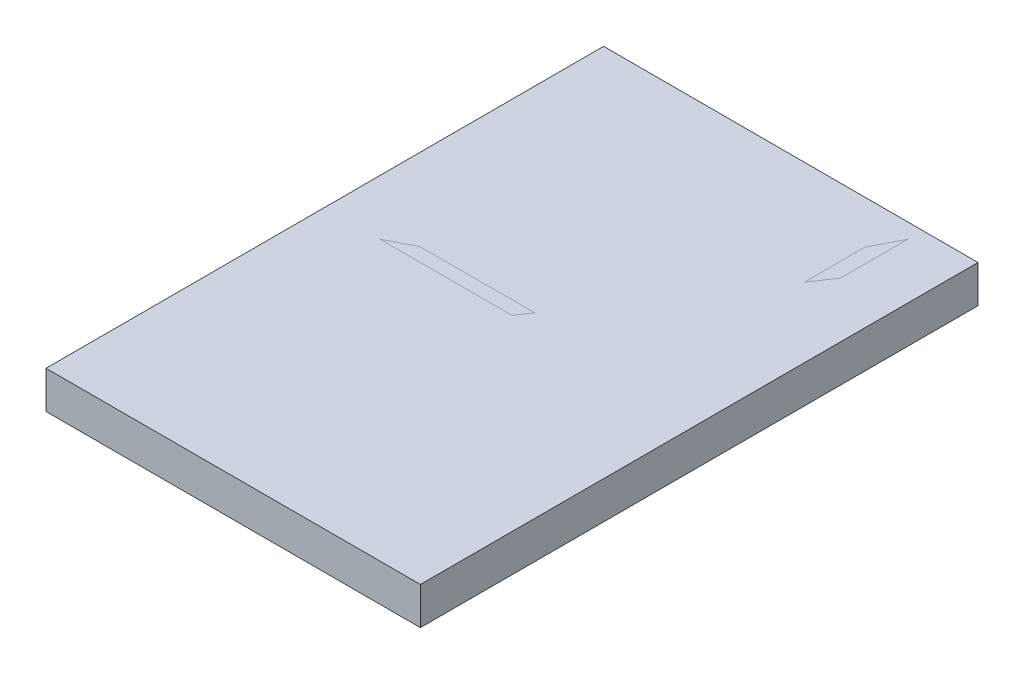
SolidWorks part; units mm, degrees
other "Stock"
other "Part"
ref_plane "Front Plane" through (0, 0, 0) normal (0, 0, 1) x (1, 0, 0)
ref_plane "Top Plane" through (0, 0, 0) normal (0, 1, 0) x (1, 0, 0)
ref_plane "Right Plane" through (0, 0, 0) normal (1, 0, 0) x (0, 0, -1)
sketch "Sketch1" plane through (0, 0, 0) normal (0, 1, 0) x (1, 0, 0)
  line L0 (28.2, 0) -> (28.2, -142.8) construction
  line L1 (0, 0) -> (56.4, 0)
  line L2 (0, 0) -> (0, -142.8)
  line L3 (0, -142.8) -> (56.4, -142.8)
  line L4 (56.4, 0) -> (56.4, -142.8)
  line L5 (0, -71.4) -> (56.4, -71.4) construction
  dimension "D1" = 56.4
  dimension "D2" = 142.8
extrude "Boss-Extrude1" add sketch "Sketch1" along normal blind 8
sketch "Sketch2" plane through (0, 8, 0) normal (0, 1, 0) x (1, 0, 0)
  line L0 (0, -71.4) -> (56.4, -71.4) construction
  line L1 (0, 0) -> (0, -142.8) construction
  line L2 (56.4, -142.8) -> (56.4, 0) construction
  line L3 (28.2, 0) -> (28.2, -142.8) construction
  line L4 (56.4, 0) -> (0, 0) construction
  line L5 (0, -142.8) -> (56.4, -142.8) construction
  line L6 (0, -43.2) -> (56.4, -43.2) construction
  circle A0 centre (28.2, -43.2) radius 16
  dimension "D2" = 32
  dimension "D1" = 28.2
extrude "Cut-Extrude1" cut sketch "Sketch2" against normal blind 6
sketch "Sketch3" plane through (0, 2, 0) normal (0, 1, 0) x (1, 0, 0)
  circle A0 centre (28.2, -43.2) radius 10
  dimension "D1" = 20
extrude "Cut-Extrude2" cut sketch "Sketch3" against normal through all
sketch "Sketch4" plane through (0, 8, 0) normal (0, 1, 0) x (1, 0, 0)
  line L0 (56.4, 0) -> (0, 0) construction
  line L1 (28.2, 0) -> (28.2, -86.1901) construction
  line L2 (0, -43.2) -> (56.4, -43.2) construction
  line L3 (0, 0) -> (0, -142.8) construction
  line L4 (56.4, -142.8) -> (56.4, 0) construction
  line L5 (0, -71.4) -> (56.4, -71.4) construction
  circle A0 centre (4.58, -19.58) radius 2
  circle A1 centre (51.82, -19.58) radius 2
  circle A2 centre (51.82, -66.82) radius 2
  circle A3 centre (4.58, -66.82) radius 2
  dimension "D4" = 4
  dimension "D1" = 23.62
  dimension "D2" = 28.2
  dimension "D3" = 23.62
extrude "Cut-Extrude3" cut sketch "Sketch4" against normal through all
sketch "Sketch5" plane through (0, 8, 0) normal (0, 1, 0) x (1, 0, 0)
  line L0 (0, -71.4) -> (56.4, -71.4) construction
  line L1 (0, 0) -> (0, -142.8) construction
  line L2 (56.4, -142.8) -> (56.4, 0) construction
  line L3 (0, -99.6) -> (56.4, -99.6) construction
  line L4 (28.2, 0) -> (28.2, -142.8) construction
  line L5 (56.4, 0) -> (0, 0) construction
  line L6 (0, -142.8) -> (56.4, -142.8) construction
  circle A0 centre (28.2, -99.6) radius 12
  point P14 (28.2, -99.6)
  dimension "D2" = 24
  dimension "D1" = 28.2
extrude "Cut-Extrude4" [suppressed] cut sketch "Sketch5" against normal through all
ref_plane "Plane1" through (0, 0, 71.4) normal (0, 0, 1) x (1, 0, 0)
mirror "Mirror1" about plane through (0, 0, 71.4) normal (0, 0, 1) of "Cut-Extrude3"
fillet "Fillet2" radius 3 4 edges at (0, 4, 0) (56.4, 4, 0) (56.4, 4, 142.8) (0, 4, 142.8)
sketch "Sketch6" plane through (0, 8, 0) normal (0, 1, 0) x (1, 0, 0)
  line L0 (56.4, -139.8) -> (56.4, -3) construction
  line L1 (0, 0) -> (56.4, 0) construction
  line L2 (0, 0) -> (0, -142.8) construction
  line L3 (0, -142.8) -> (56.4, -142.8) construction
  line L4 (56.4, 0) -> (56.4, -142.8) construction
  line L5 (53.4, 0) -> (3, 0) construction
  line L6 (0, -3) -> (0, -139.8) construction
  line L7 (3, -142.8) -> (53.4, -142.8) construction
  line L8 (0, -71.4) -> (56.4, -71.4) construction
  line L9 (28.2, 0) -> (28.2, -142.8) construction
  line L10 (0, 0) -> (56.4, -142.8) construction
  line L11 (0, -142.8) -> (56.4, 0) construction
  line L13 (-11.8, -11.825) -> (68.2, -11.825)
  line L14 (-11.8, -11.825) -> (-11.8, -130.975)
  line L15 (-11.8, -130.975) -> (68.2, -130.975)
  line L16 (68.2, -11.825) -> (68.2, -130.975)
  line L17 (-11.8, -11.825) -> (68.2, -130.975) construction
  line L18 (-11.8, -130.975) -> (68.2, -11.825) construction
  point P16 (28.2, -71.4)
  dimension "D1" = 80
  dimension "D2" = 119.15
extrude "Boss-Extrude2" add sketch "Sketch6" against normal blind 8 separate body
sketch "Sketch8" plane through (0, 8, 0) normal (0, 1, 0) x (1, 0, 0)
  line L0 (-11.8, -11.825) -> (-11.8, -130.975) construction
  line L1 (-11.8, -130.975) -> (68.2, -130.975) construction
  line L2 (-11.8, -11.825) -> (-11.8, -130.975)
  line L3 (-11.8, -130.975) -> (68.2, -130.975)
sketch "Sketch9" plane through (0, 8, 0) normal (0, 1, 0) x (1, 0, 0)
  line L0 (53.4, 0) -> (3, 0) construction
  line L1 (0, -3) -> (0, -139.8) construction
  line L2 (56.4, -139.8) -> (56.4, -3) construction
  line L3 (28.2, 0) -> (28.2, -70.1416) construction
  circle A0 centre (7.5, -7.5) radius 2
  circle A1 centre (28.2, -7.5) radius 2
  circle A2 centre (48.9, -7.5) radius 2
  dimension "D1" = 4
  dimension "D2" = 4
  dimension "D3" = 4
  dimension "D4" = 7.5
  dimension "D5" = 7.5
  dimension "D6" = 7.5
  dimension "D7" = 7.5
  dimension "D8" = 7.5
extrude "Cut-Extrude5" cut sketch "Sketch9" against normal blind 10
mirror "Mirror2" about plane through (0, 0, 71.4) normal (0, 0, 1) of "Cut-Extrude5"
other "SurfaceCut1"
ref_plane "Plane2" through (0, 0, 15) normal (0, 0, 1) x (1, 0, 0)
other "SurfaceCut2"
